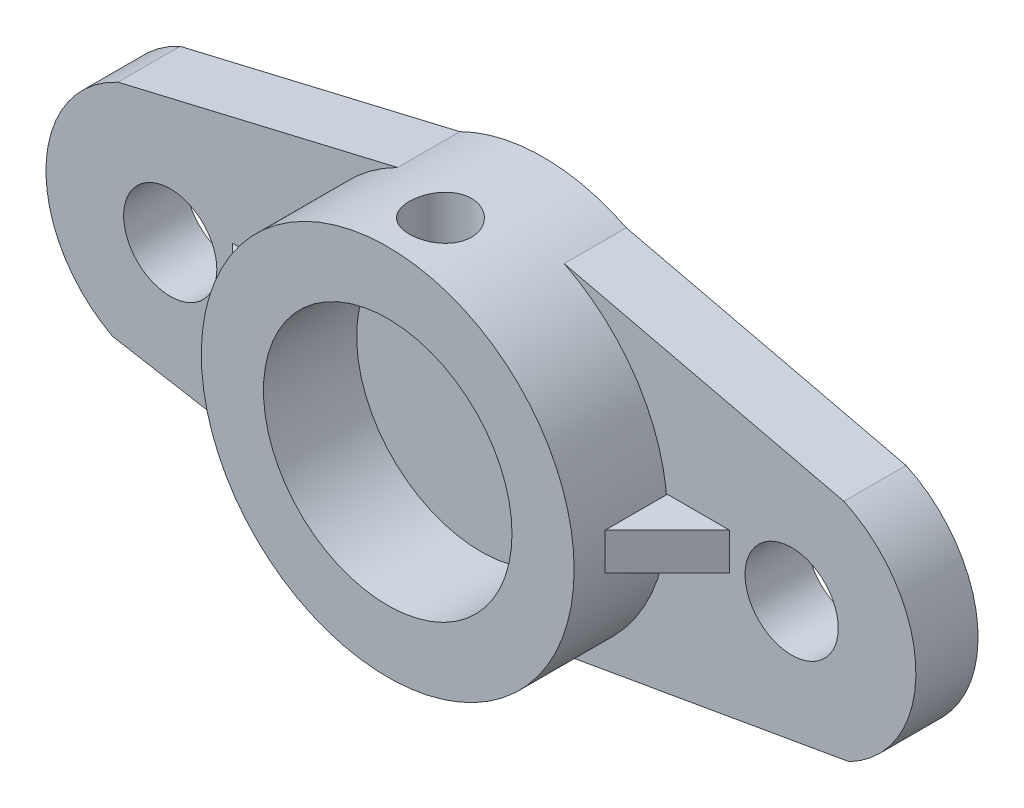
SolidWorks part; units mm, degrees
ref_plane "Front Plane" through (0, 0, 0) normal (0, 0, 1) x (1, 0, 0)
ref_plane "Top Plane" through (0, 0, 0) normal (0, 1, 0) x (1, 0, 0)
ref_plane "Right Plane" through (0, 0, 0) normal (1, 0, 0) x (0, 0, -1)
sketch "Sketch1" plane through (0, 0, 0) normal (0, 0, 1) x (1, 0, 0)
  line L0 (-13.4021, 26.84) -> (-58.4131, 16.227)
  line L1 (59.2736, -19.6375) -> (10.1784, -28.2206)
  line L2 (-59.2736, -19.6375) -> (-10.1784, -28.2206)
  line L3 (0, 30) -> (0, -30) construction
  line L4 (13.4021, 26.84) -> (58.4131, 16.227)
  circle A0 centre (0, 0) radius 20 construction
  circle A1 centre (0, 0) radius 30
  arc A2 (-58.4131, 16.227) -> (-59.2736, -19.6375) centre (-50, -1.9174) ccw
  circle A3 centre (-50, -1.9174) radius 7.5
  circle A4 centre (50, -1.9174) radius 7.5
  arc A5 (58.4131, 16.227) -> (59.2736, -19.6375) centre (50, -1.9174) cw
  point P6 (0, 0)
  point P10 (0, 0)
  point P16 (0, 30)
  point P17 (0, 30)
  dimension "D1" = 60
  dimension "D2" = 40
  dimension "D3" = 20
  dimension "D4" = 15
  dimension "D5" = 50
extrude "Boss-Extrude1" add sketch "Sketch1" along normal blind 10 contours L0 A2 L2 A1 A3 | L0 A1 L2 L1 L4 | A5 L4 A1 L1 A4
sketch "Sketch2" plane through (0, 0, 10) normal (0, 0, 1) x (1, 0, 0)
  circle A0 centre (0, 0) radius 30
  circle A1 centre (0, 0) radius 20
  dimension "D1" = 40
  dimension "D2" = 60
extrude "Boss-Extrude2" add sketch "Sketch2" along normal blind 15
sketch "Sketch7" plane through (0, 0, 0) normal (0, 1, 0) x (1, 0, 0)
  line L0 (-30, -10) -> (-30, -20)
  line L2 (-30, -20) -> (-40, -10)
  line L4 (-40, -10) -> (-30, -10)
  line L5 (0, 20.9988) -> (0, -41.5098) construction
  line L6 (30, -20) -> (40, -10)
  line L7 (30, -10) -> (30, -20)
  line L8 (40, -10) -> (30, -10)
  dimension "D1" = 10
  dimension "D2" = 10
extrude "Boss-Extrude9" add sketch "Sketch7" along normal mid plane 6 separate body
ref_plane "Plane1" through (0, 30, 0) normal (0, 1, 0) x (1, 0, 0)
sketch "Sketch9" plane through (0, 30, 0) normal (0, 1, 0) x (1, 0, 0)
  circle A0 centre (0, -16.5173) radius 5
  point P2 (0, -11.8743)
  point P3 (0, -16.6949)
  point P4 (0, -14.8615)
  point P5 (0, -16.5173)
  dimension "D1" = 10
extrude "Cut-Extrude1" cut sketch "Sketch9" against normal blind 12
